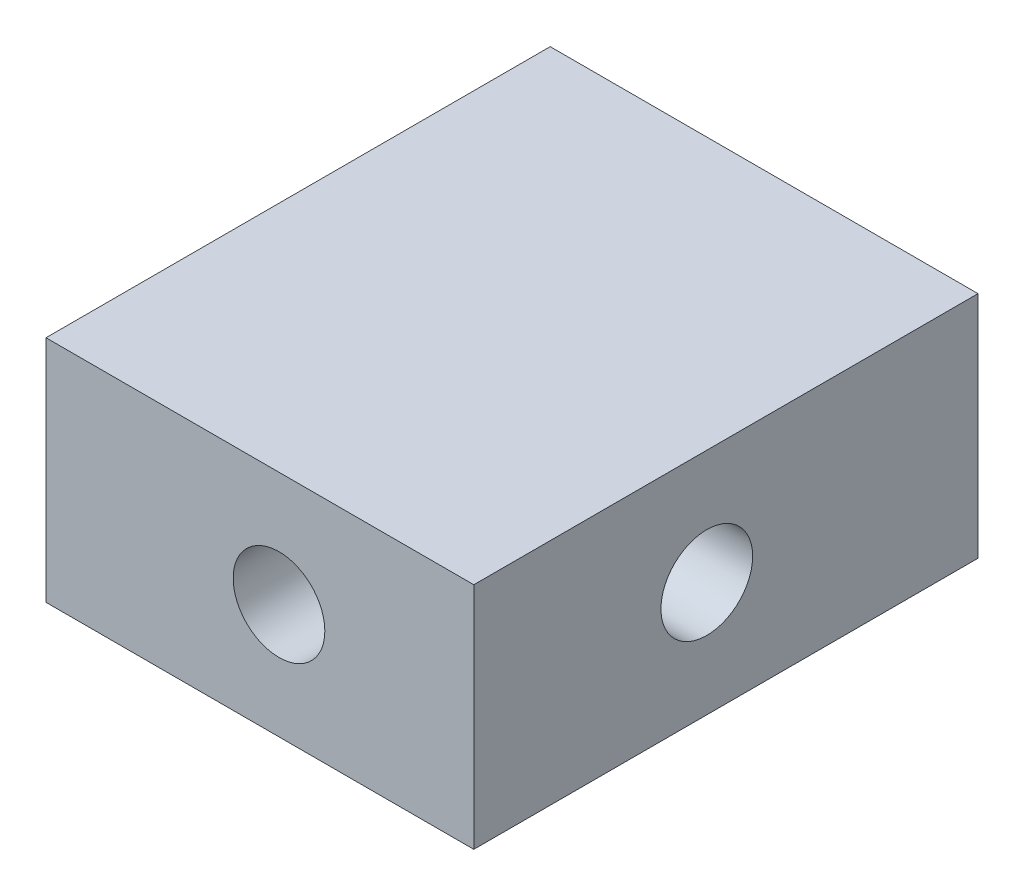
SolidWorks part; units mm, degrees
ref_plane "前视基准面" through (0, 0, 0) normal (0, 0, 1) x (1, 0, 0)
ref_plane "上视基准面" through (0, 0, 0) normal (0, 1, 0) x (1, 0, 0)
ref_plane "右视基准面" through (0, 0, 0) normal (1, 0, 0) x (0, 0, -1)
sketch "草图1" plane through (0, 0, 0) normal (0, 1, 0) x (1, 0, 0)
  line L1 (0, 0) -> (28, 0)
  line L2 (0, 0) -> (0, -33)
  line L3 (0, -33) -> (28, -33)
  line L4 (28, 0) -> (28, -33)
  dimension "D1" = 28
  dimension "D2" = 33
extrude "凸台-拉伸1" add sketch "草图1" along normal blind 15
sketch "草图2" plane through (0, 0, 33) normal (0, 0, 1) x (1, 0, 0)
  line L0 (0, 15) -> (0, 0) construction
  line L1 (0, 0) -> (28, 0) construction
  circle A0 centre (15.25, 7.5) radius 3
  dimension "D1" = 15.25
  dimension "D2" = 7.5
  dimension "D3" = 6
extrude "切除-拉伸1" cut sketch "草图2" against normal blind 5
sketch "草图3" plane through (28, 0, 0) normal (1, 0, 0) x (0, 0, -1)
  line L0 (0, 15) -> (0, 0) construction
  line L1 (-33, 0) -> (0, 0) construction
  circle A0 centre (-17.75, 7.5) radius 3
  dimension "D1" = 17.75
  dimension "D2" = 6
  dimension "D3" = 7.5
extrude "切除-拉伸2" cut sketch "草图3" against normal blind 5
sketch "草图4" plane through (0, 15, 0) normal (0, 1, 0) x (1, 0, 0)
  line L0 (0, 0) -> (0, -33) construction
  line L1 (2, -26) -> (21, -26)
  line L2 (2, -26) -> (2, -2)
  line L3 (2, -2) -> (21, -2)
  line L4 (21, -26) -> (21, -2)
  line L5 (28, 0) -> (0, 0) construction
  line L6 (23, -20.75) -> (23, -14.75) construction
  line L7 (12.25, -28) -> (18.25, -28) construction
  dimension "D1" = 2
  dimension "D2" = 2
  dimension "D3" = 2
  dimension "D4" = 2
